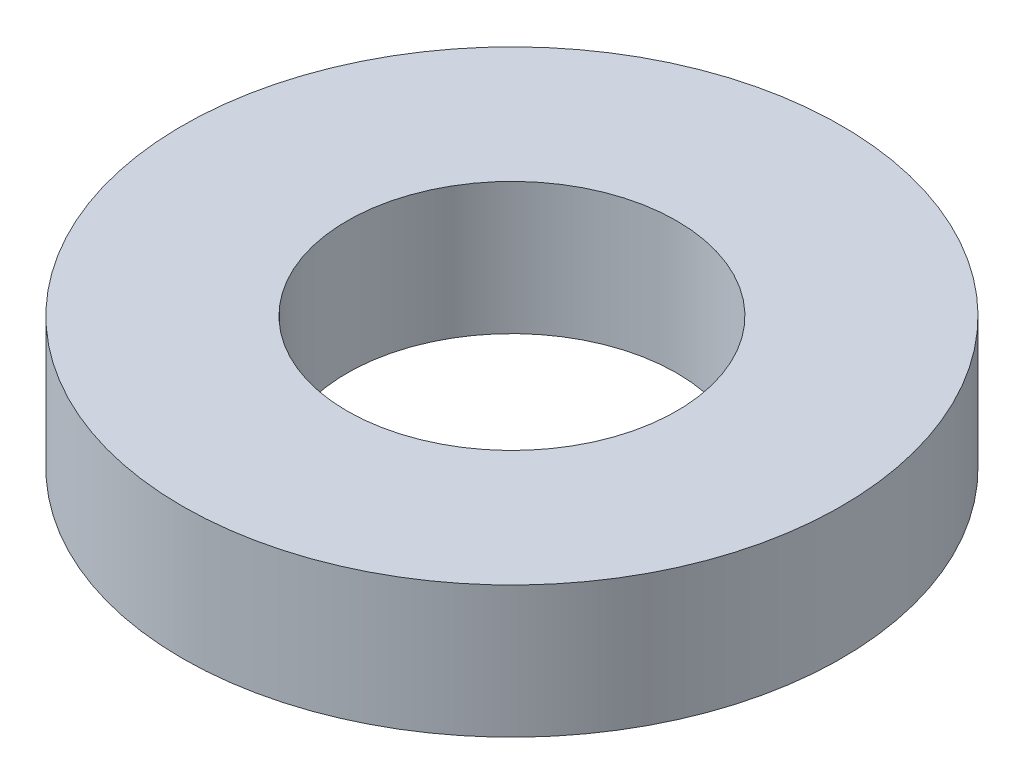
SolidWorks part; units mm, degrees
ref_plane "前视基准面" through (0, 0, 0) normal (0, 0, 1) x (1, 0, 0)
ref_plane "上视基准面" through (0, 0, 0) normal (0, 1, 0) x (1, 0, 0)
ref_plane "右视基准面" through (0, 0, 0) normal (1, 0, 0) x (0, 0, -1)
other "Configuration Table"
sketch "草图1" plane through (0, 0, 0) normal (0, 1, 0) x (1, 0, 0)
  circle A0 centre (0, 0) radius 25
  circle A1 centre (0, 0) radius 50
  dimension "D1" = 50
  dimension "D2" = 100
extrude "凸台-拉伸1" add sketch "草图1" along normal mid plane 20
